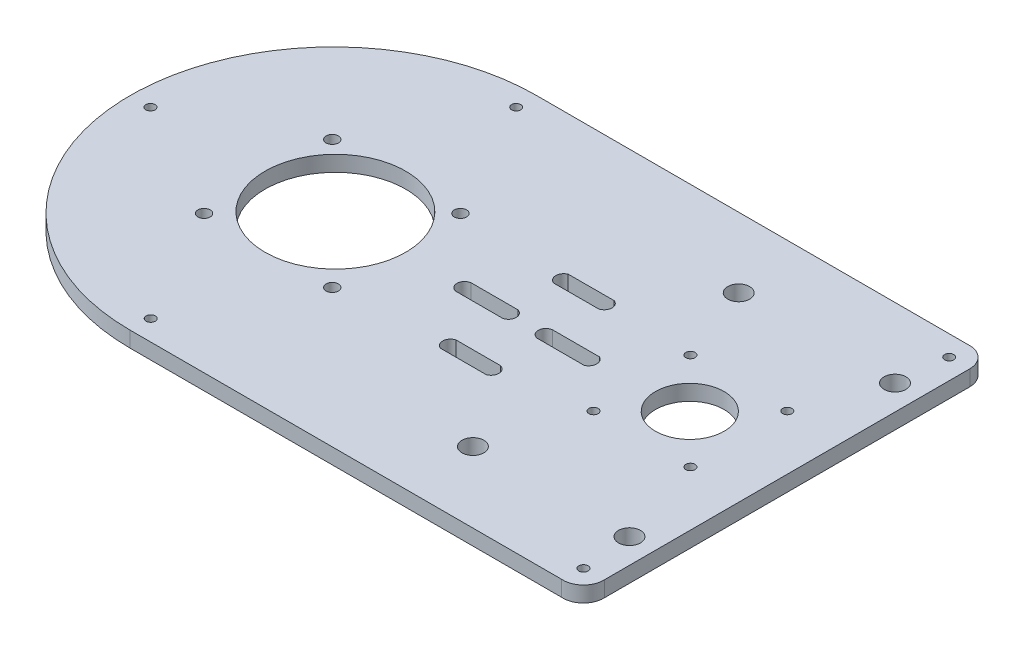
SolidWorks part; units mm, degrees
ref_plane "Front Plane" through (0, 0, 0) normal (0, 0, 1) x (1, 0, 0)
ref_plane "Top Plane" through (0, 0, 0) normal (0, 1, 0) x (1, 0, 0)
ref_plane "Right Plane" through (0, 0, 0) normal (1, 0, 0) x (0, 0, -1)
sketch "Sketch2" plane through (0, 0, 0) normal (0, 1, 0) x (1, 0, 0)
  line L0 (-89.9114, 0) -> (98.189, 0) construction
  line L1 (-52.202, 61.0827) -> (85.798, 61.0827)
  line L2 (92.798, 54.7477) -> (92.798, -62.2523)
  line L3 (85.798, -68.9173) -> (-52.202, -68.9173)
  arc A0 (85.798, 61.0827) -> (92.798, 54.7477) centre (86.2996, 54.6021) cw
  arc A1 (92.798, -62.2523) -> (85.798, -68.9173) centre (86.2996, -62.4357) cw
  arc A2 (-52.202, 61.0827) -> (-52.202, -68.9173) centre (-52.202, -3.9173) ccw
  dimension "D7" = 65
  dimension "D8" = 6.5
  dimension "D9" = 6.501
  dimension "D1" = 145
  dimension "D2" = 130
  dimension "D3" = 117
  dimension "D4" = 138
  dimension "D5" = 138
  dimension "D6" = 145
extrude "Boss-Extrude1" add sketch "Sketch2" along normal blind 5
sketch "Sketch3" plane through (0, 5, 0) normal (0, 1, 0) x (1, 0, 0)
  line L0 (92.798, -3.7523) -> (-117.202, -3.9173) construction
  line L1 (92.798, -62.2523) -> (92.798, 54.7477) construction
  line L2 (-52.202, -68.9173) -> (85.798, -68.9173) construction
  line L3 (85.798, 61.0827) -> (-52.202, 61.0827) construction
  arc A0 (-52.202, 61.0827) -> (-52.202, -68.9173) centre (-52.202, -3.9173) ccw construction
  circle A1 centre (86.298, 54.5827) radius 1.475
  circle A2 centre (-52.202, 54.5827) radius 1.475
  circle A3 centre (-110.702, -3.9122) radius 1.475
  circle A4 centre (86.298, -62.4173) radius 1.475
  circle A5 centre (-52.11, -62.4173) radius 1.475
  dimension "D1" = 58.5
  dimension "D2" = 2.95
  dimension "D4" = 6.5
  dimension "D5" = 2.95
  dimension "D6" = 6.5
  dimension "D3" = 6.5
  dimension "D8" = 2.95
  dimension "D9" = 2.95
  dimension "D10" = 2.95
  dimension "138.5" = 138.5
  dimension "D7" = 6.5
extrude "Cut-Extrude1" cut sketch "Sketch3" against normal through all
sketch "Sketch4" plane through (0, 5, 0) normal (0, 1, 0) x (1, 0, 0)
  line L1 (2.3533, 16.6504) -> (17.0357, 16.6734)
  line L2 (2.5264, 11.8642) -> (16.842, 11.8867)
  line L5 (92.798, -62.2523) -> (92.798, 54.7477) construction
  line L7 (-10.778, -1.2604) -> (4.222, -1.2604)
  line L8 (15.222, -1.2604) -> (30.222, -1.2604)
  line L9 (-10.9108, -6.0604) -> (4.222, -6.0604)
  line L10 (15.0892, -6.0604) -> (30.1475, -6.0604)
  line L13 (2.5511, -19.5107) -> (16.8667, -19.5107)
  line L14 (2.3855, -24.2971) -> (17.0679, -24.2971)
  circle A0 centre (-52.1815, -3.2803) radius 22.5
  circle A1 centre (59.8101, -1.9112) radius 11
  circle A3 centre (-72.707, 16.2405) radius 1.975
  circle A4 centre (-72.707, -24.7695) radius 1.975
  circle A5 centre (-31.697, -24.7695) radius 1.975
  circle A6 centre (-31.697, 16.2405) radius 1.975
  circle A17 centre (44.3101, 13.7883) radius 1.475
  circle A18 centre (44.3101, -17.2117) radius 1.475
  circle A19 centre (75.3101, -17.2117) radius 1.475
  circle A20 centre (75.3101, 13.7883) radius 1.475
  circle A21 centre (84.798, 38.7415) radius 3.5
  circle A23 centre (34.798, 38.7415) radius 3.5
  circle A24 centre (84.8648, -46.2585) radius 3.5
  circle A25 centre (34.8648, -46.3371) radius 3.5
  arc A34 (4.222, -1.2604) -> (4.222, -6.0604) centre (3.522, -3.6604) cw
  arc A36 (16.8667, -19.5107) -> (17.0679, -24.2971) centre (16.2521, -21.9339) cw
  arc A38 (-10.778, -1.2604) -> (-10.9108, -6.0604) centre (-10.4633, -3.6709) ccw
  arc A39 (15.222, -1.2604) -> (15.0892, -6.0604) centre (15.5367, -3.6709) ccw
  arc A40 (30.222, -1.2604) -> (30.1475, -6.0604) centre (29.1646, -3.6446) cw
  arc A41 (2.5511, -19.5107) -> (2.3855, -24.2971) centre (3.3377, -21.9339) ccw
  arc A43 (2.5264, 11.8642) -> (2.3533, 16.6504) centre (3.3093, 14.2887) cw
  arc A44 (16.842, 11.8867) -> (17.0357, 16.6734) centre (16.2236, 14.309) ccw
  point P14 (0, 0)
  point P44 (22.722, -1.2604)
  dimension "D2" = 45
  dimension "D3" = 22
  dimension "D4" = 3.95
  dimension "D5" = 3.95
  dimension "D11" = 2.5
  dimension "D14" = 2.95
  dimension "D15" = 2.95
  dimension "D18" = 7
  dimension "D20" = 7
  dimension "D24" = 2.95
  dimension "D25" = 2.95
  dimension "D26" = 15.5
  dimension "D8" = 11
  dimension "D12" = 3.95
  dimension "D13" = 3.95
  dimension "D6" = 41.01
  dimension "D7" = 41.01
  dimension "D9" = 15
  dimension "D10" = 15
  dimension "D16" = 31
  dimension "D17" = 31
  dimension "D19" = 8
  dimension "D21" = 50
  dimension "D22" = 85
  dimension "D23" = 112
extrude "Cut-Extrude2" cut sketch "Sketch4" against normal through all
